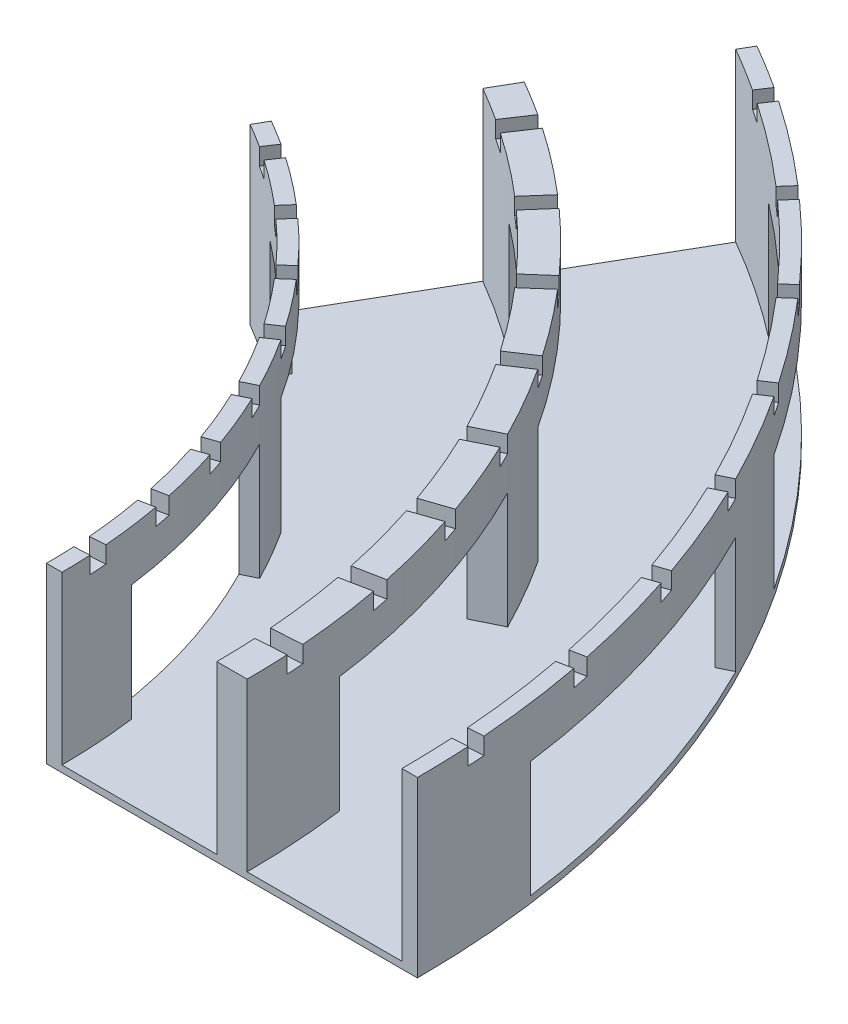
SolidWorks part; units mm, degrees
ref_plane "Ebene vorne" through (0, 0, 0) normal (0, 0, 1) x (1, 0, 0)
ref_plane "Ebene oben" through (0, 0, 0) normal (0, 1, 0) x (1, 0, 0)
ref_plane "Ebene rechts" through (0, 0, 0) normal (1, 0, 0) x (0, 0, -1)
sketch "Skizze1" plane through (0, 0, 0) normal (0, 1, 0) x (1, 0, 0)
  line L0 (165, 0) -> (169.6, 0) construction
  line L1 (84.8, 146.8779) -> (82.5, 142.8942) construction
  line L2 (0, 0) -> (84.8, 146.8779) construction
  line L3 (270.4, 0) -> (275, 0) construction
  line L4 (137.5, 238.157) -> (135.2, 234.1733) construction
  line L5 (169.6, 0) -> (270.4, 0) construction
  line L6 (84.8, 146.8779) -> (135.2, 234.1733) construction
  line L7 (112.25, 194.4227) -> (107.75, 186.6285) construction
  line L8 (224.5, 0) -> (215.5, 0) construction
  line L9 (112.25, 194.4227) -> (110, 190.5256) construction
  line L10 (165, 0) -> (169.6, 0)
  line L11 (82.5, 142.8942) -> (84.8, 146.8779)
  line L13 (215.5, 0) -> (224.5, 0)
  line L15 (112.25, 194.4227) -> (107.75, 186.6285)
  line L16 (135.2, 234.1733) -> (137.5, 238.157)
  line L17 (270.4, 0) -> (275, 0)
  arc A0 (165, 0) -> (82.5, 142.8942) centre (0, 0) ccw
  arc A1 (169.6, 0) -> (84.8, 146.8779) centre (0, 0) ccw
  arc A2 (270.4, 0) -> (135.2, 234.1733) centre (0, 0) ccw
  arc A3 (275, 0) -> (137.5, 238.157) centre (0, 0) ccw
  arc A4 (220, 0) -> (110, 190.5256) centre (0, 0) ccw construction
  arc A5 (215.5, 0) -> (107.75, 186.6285) centre (0, 0) ccw
  arc A6 (224.5, 0) -> (112.25, 194.4227) centre (0, 0) ccw
  point P10 (83.65, 144.8861)
  dimension "D1" = 165
  dimension "D4" = 275
  dimension "D2" = 4.6
  dimension "D3" = 60
  dimension "D5" = 4.5
  dimension "D6" = 4.5
extrude "Aufsatz-Linear austragen1" add sketch "Skizze1" along normal blind 51.5
sketch "Skizze2" plane through (0, 51.5, 0) normal (0, 1, 0) x (1, 0, 0)
  line L0 (0, 0) -> (275, 0) construction
  line L1 (0, 0) -> (274.4112, 17.9859) construction
  line L2 (164.4643, 13.2849) -> (274.2364, 20.4798)
  line L3 (164.7913, 8.2956) -> (274.5634, 15.4905)
  line L4 (161.3233, 34.6382) -> (269.2171, 56.0996)
  line L5 (162.2987, 29.7342) -> (270.1925, 51.1957)
  line L6 (0, 0) -> (161.8296, 32.1899) construction
  line L7 (157.0291, 50.6641) -> (261.1986, 86.0249)
  line L8 (155.4219, 55.3987) -> (259.5914, 90.7595)
  line L9 (149.0727, 70.7271) -> (247.7355, 119.3822)
  line L10 (146.8613, 75.2114) -> (245.5241, 123.8665)
  line L11 (138.5657, 89.5799) -> (230.0336, 150.6968)
  line L12 (135.7878, 93.7372) -> (227.2558, 154.8542)
  line L13 (125.6877, 106.9) -> (208.3958, 179.433)
  line L14 (122.391, 110.6592) -> (205.099, 183.1922)
  line L15 (110.6592, 122.391) -> (183.1922, 205.099)
  line L16 (106.9, 125.6877) -> (179.433, 208.3958)
  line L17 (93.7372, 135.7878) -> (154.8542, 227.2558)
  line L18 (89.5799, 138.5657) -> (150.6968, 230.0336)
  line L21 (0, 0) -> (156.2435, 53.0375) construction
  line L22 (0, 0) -> (147.984, 72.9776) construction
  line L23 (0, 0) -> (137.1925, 91.6691) construction
  line L24 (0, 0) -> (124.0536, 108.7921) construction
  line L25 (0, 0) -> (108.7921, 124.0536) construction
  line L26 (91.6691, 137.1925) -> (0, 0) construction
  arc A0 (275, 0) -> (137.5, 238.157) centre (0, 0) ccw construction
  arc A1 (164.7913, 8.2956) -> (164.4643, 13.2849) centre (0, 0) ccw
  arc A2 (165, 0) -> (82.5, 142.8942) centre (0, 0) ccw construction
  arc A3 (274.5634, 15.4905) -> (274.2364, 20.4798) centre (0, 0) ccw
  arc A4 (162.2987, 29.7342) -> (161.3233, 34.6382) centre (0, 0) ccw
  arc A5 (270.1925, 51.1957) -> (269.2171, 56.0996) centre (0, 0) ccw
  arc A6 (157.0291, 50.6641) -> (155.4219, 55.3987) centre (0, 0) ccw
  arc A7 (261.1986, 86.0249) -> (259.5914, 90.7595) centre (0, 0) ccw
  arc A8 (149.0727, 70.7271) -> (146.8613, 75.2114) centre (0, 0) ccw
  arc A9 (247.7355, 119.3822) -> (245.5241, 123.8665) centre (0, 0) ccw
  arc A10 (138.5657, 89.5799) -> (135.7878, 93.7372) centre (0, 0) ccw
  arc A11 (230.0336, 150.6968) -> (227.2558, 154.8542) centre (0, 0) ccw
  arc A12 (125.6877, 106.9) -> (122.391, 110.6592) centre (0, 0) ccw
  arc A13 (208.3958, 179.433) -> (205.099, 183.1922) centre (0, 0) ccw
  arc A14 (110.6592, 122.391) -> (106.9, 125.6877) centre (0, 0) ccw
  arc A15 (183.1922, 205.099) -> (179.433, 208.3958) centre (0, 0) ccw
  arc A16 (93.7372, 135.7878) -> (89.5799, 138.5657) centre (0, 0) ccw
  arc A17 (154.8542, 227.2558) -> (150.6968, 230.0336) centre (0, 0) ccw
  point P22 (0, 0)
  point P52 (0, 0)
  dimension "D1" = 5
  dimension "D2" = 2.5
  dimension "D3" = 3.75
  dimension "D5" = 7.5
  dimension "D7" = 7.5
  dimension "D6" = 7.5
  dimension "D8" = 7.5
  dimension "D9" = 7.5
  dimension "D10" = 7.5
  dimension "D11" = 7.5
  dimension "D12" = 5
  dimension "D13" = 5
  dimension "D14" = 5
  dimension "D15" = 5
  dimension "D16" = 5
  dimension "D17" = 5
  dimension "D4" = 2
extrude "Schnitt-Linear austragen1" cut sketch "Skizze2" against normal blind 5
sketch "Skizze4" plane through (0, 0, 0) normal (0, -1, 0) x (1, 0, 0)
  line L0 (165, 0) -> (275, 0)
  line L1 (82.5, -142.8942) -> (137.5, -238.157)
  line L2 (112.25, -194.4227) -> (107.75, -186.6285) construction
  line L3 (215.5, 0) -> (224.5, 0) construction
  arc A0 (137.5, -238.157) -> (275, 0) centre (0, 0) ccw
  arc A1 (82.5, -142.8942) -> (165, 0) centre (0, 0) ccw
  arc A2 (82.5, -142.8942) -> (165, 0) centre (0, 0) ccw construction
  arc A3 (137.5, -238.157) -> (275, 0) centre (0, 0) ccw construction
extrude "Aufsatz-Linear austragen2" add sketch "Skizze4" against normal blind 2
sketch "Skizze5" plane through (0, 51.5, 0) normal (0, 1, 0) x (1, 0, 0)
  line L0 (100.4456, 130.9033) -> (167.4094, 218.1722)
  line L1 (163.5884, 21.5368) -> (272.6473, 35.8947)
  line L2 (138.5657, 89.5799) -> (230.0336, 150.6968)
  line L3 (146.8613, 75.2114) -> (245.5241, 123.8665)
  arc A5 (106.9, 125.6877) -> (93.7372, 135.7878) centre (0, 0) ccw construction
  arc A6 (179.433, 208.3958) -> (154.8542, 227.2558) centre (0, 0) ccw construction
  arc A7 (164.4643, 13.2849) -> (162.2987, 29.7342) centre (0, 0) ccw construction
  arc A8 (274.2364, 20.4798) -> (270.1925, 51.1957) centre (0, 0) ccw construction
  arc A12 (163.5884, 21.5368) -> (146.8613, 75.2114) centre (0, 0) ccw
  arc A13 (138.5657, 89.5799) -> (100.4456, 130.9033) centre (0, 0) ccw
  arc A14 (272.6473, 35.8947) -> (245.5241, 123.8665) centre (0, 0) ccw
  arc A15 (230.0336, 150.6968) -> (167.4094, 218.1722) centre (0, 0) ccw
  point P2 (0, 0)
  point P20 (0, 0)
extrude "Schnitt-Linear austragen2" cut sketch "Skizze5" against normal up to surface (34.5 mm away) from offset 15 up to face at (155.5828, 2, -89.8258)
equation "\"D6@Skizze1\"=\"D5@Skizze1\""
equation "\"D2@Skizze2\"=\"D1@Skizze2\"/2"
